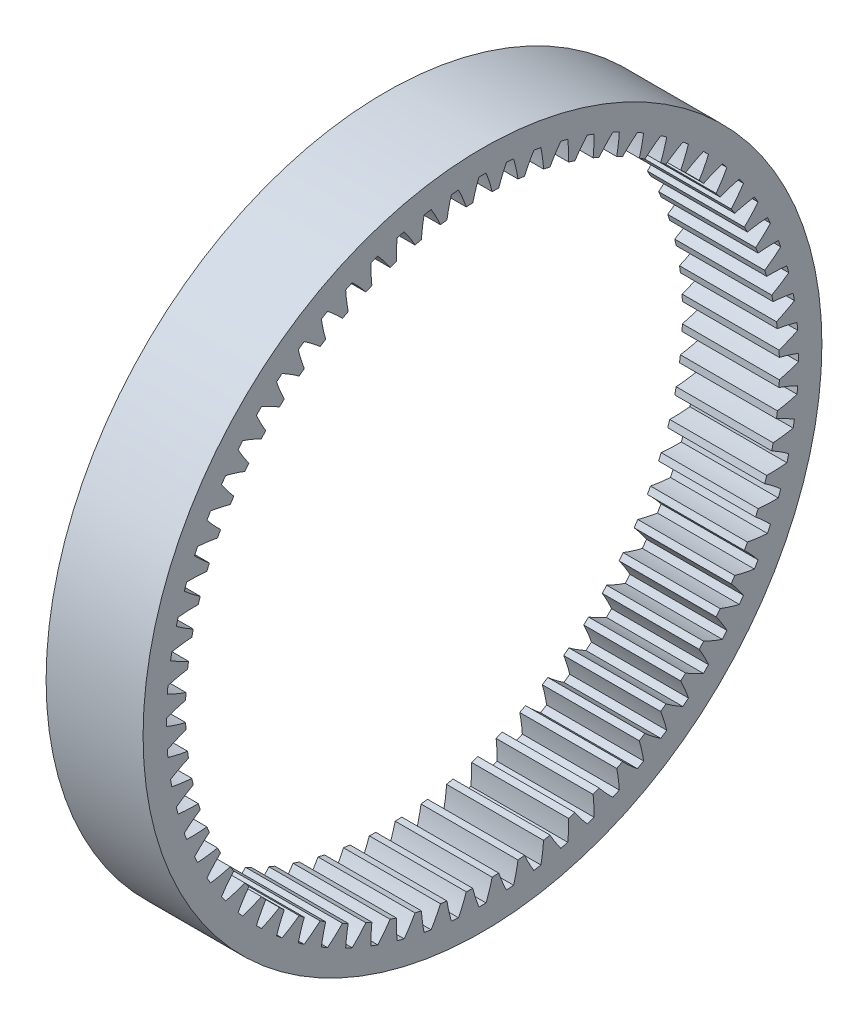
SolidWorks part; units mm, degrees
ref_plane "Plane1" through (0, 0, 0) normal (0, 0, 1) x (1, 0, 0)
ref_plane "Plane2" through (0, 0, 0) normal (0, 1, 0) x (1, 0, 0)
ref_plane "Plane3" through (0, 0, 0) normal (1, 0, 0) x (0, 0, -1)
sketch "HoldingSke" plane through (0, 0, 0) normal (0, 1, 0) x (1, 0, 0)
  line L0 (0, 0) -> (0.1766, -0.5435)
  line L1 (-15, 0) -> (100, 0) construction
  line L2 (0, 0) -> (-2.1039, 2.3779)
  line L3 (0, 0) -> (-11.863, 4.5341)
  line L4 (0, 0) -> (2.6687, 8.2133)
  line L5 (0, 0) -> (-23.7986, -8.8762)
  line L6 (0, 0) -> (-10.5278, -7.1032)
  line L7 (-2.1039, 2.3779) -> (3.3635, 27.1825)
  line L8 (-76.2, 4.1279) -> (-54.61, 4.1279)
  line L9 (-67.7845, 28.3722) -> (-49.3413, 33.142)
  line L10 (-76.2, 71.12) -> (104.1128, 71.12)
  line L11 (0, 0) -> (-20, 0)
  line L12 (-76.2, 101.6) -> (-76.147, 101.6)
  line L13 (24.9733, 27.94) -> (52.9518, 28.4284)
  line L14 (24.9733, 27.94) -> (24.9743, 27.94)
  line L15 (24.9733, 27.94) -> (100.4006, 29.5858)
  circle A0 centre (0, 0) radius 70
  circle A1 centre (0, 0) radius 12.7
  circle A2 centre (0, 0) radius 12.7
  dimension "MHD" = 25.4
  dimension "Hub_dia" = 25.4
  dimension "Diameter" = 140
  dimension "Num_teeth" = 72
  dimension "Pitch" = 0.5714
  dimension "Overall_len" = 25.4
  dimension "Show_teeth" = 72
  dimension "Thickness" = 12.7
  dimension "OAL" = 25.4001
  dimension "T_dim" = 21.59
  dimension "Ap" = 14.5
  dimension "H" = 19.05
  dimension "Pitch_radius" = 180.3128
  dimension "Width" = 20
  dimension "Backlash" = 0.053
  dimension "Addendum_fac" = 1
  dimension "Dedendum_fac" = 1.25
  dimension "Clearance_fac" = 0.25
  dimension "Dedendum_add" = 0.001
  dimension "Module" = 1.75
sketch "BasProSke" plane through (0, 0, 0) normal (0, 1, 0) x (1, 0, 0)
  line L0 (-10, 0) -> (60, 0) construction
  line L1 (0, 61.25) -> (0, 70)
  line L2 (0, 61.25) -> (20, 61.25)
  line L3 (20, 61.25) -> (20, 70)
  line L4 (20, 70) -> (0, 70)
  dimension "Diameter" = 140
  dimension "Thickness" = 20
  dimension "Inside_diameter" = 122.5
revolve "Base-Revolve" add sketch "BasProSke" angle 360 about L0
sketch "TooCutSke" plane through (0, 0, 0) normal (1, 0, 0) x (0, 0, -1)
  line L3 (1.5068, 62.982) -> (1.5068, 53.6633) construction
  line L4 (0, 0) -> (0, 59.563) construction
  line L5 (0, 0) -> (-2.9804, 68.2625) construction
  line L6 (-28.5939, 53.6978) -> (35.4123, 56.4924) construction
  circle A0 centre (0, 0) radius 63 construction
  circle A1 centre (0, 0) radius 65.1885 construction
  circle A2 centre (0, 0) radius 54.894 construction
  circle A3 centre (0, 0) radius 61.2246 construction
  arc A4 (2.0017, 61.1919) -> (0.7371, 65.1843) centre (-28.5939, 53.6978) ccw
  arc A5 (2.0017, 61.1919) -> (-2.0017, 61.1919) centre (0, 0) ccw
  arc A6 (0.7371, 65.1843) -> (-0.7371, 65.1843) centre (0, 0) ccw
  arc A7 (-0.7371, 65.1843) -> (-2.0017, 61.1919) centre (28.5939, 53.6978) ccw
  dimension "Pitch_dia" = 126
  dimension "Base_dia" = 109.7879
  dimension "Root_dia" = 130.377
  dimension "Overcut_dia" = 122.4492
  dimension "Flank_rad" = 31.5
  dimension "Half_ang" = 2.5
  dimension "Half_CT" = 1.5068
extrude "ToothCut" cut sketch "TooCutSke" along normal through all
fillet "Breaks" [suppressed] radius 0.175
fillet "RootFillets" [suppressed] radius 0.4385
pattern_circular "TeethCuts" count 72 every 5 about axis through (-10, 0, 0) along (1, 0, 0) of "RootFillets", "Breaks", "ToothCut"
equation "' \"Module@HoldingSke\" = 6.35"
equation "' \"Num_teeth@HoldingSke\" = 24"
equation "' \"Ap@HoldingSke\" =  14.5"
equation "' \"Ap@HoldingSke\" = 14.5"
equation "' \"Width@HoldingSke\" = 12"
equation "' \"Diameter@HoldingSke\" = 8 * 25.4"
equation "' \"Show_teeth@HoldingSke\" = 100"
equation "' \"Backlash@HoldingSke\" = 0.009 * 25.4"
equation "' \"Addendum_fac@HoldingSke\" = 1.0"
equation "' \"Dedendum_fac@HoldingSke\" = 1.25"
equation "' \"Dedendum_add@HoldingSke\" = 0.00005 * 25.4"
equation "' \"Clearance_fac@HoldingSke\" = 0.25"
equation "\"Pitch@HoldingSke\" = 1 / \"Module@HoldingSke\" "
equation "\"Overcut_dia@TooCutSke\" = (\"Num_teeth@HoldingSke\" - 2 * \"Addendum_fac@HoldingSke\") / \"Pitch@HoldingSke\" - 0.002 * 25.4"
equation "\"Pitch_dia@TooCutSke\" = \"Num_teeth@HoldingSke\" / \"Pitch@HoldingSke\""
equation "\"Base_dia@TooCutSke\" = \"Num_teeth@HoldingSke\" / \"Pitch@HoldingSke\" * cos((\"Ap@HoldingSke\"  * 3.14159265 / 180)) * 0.90"
equation "\"Root_dia@TooCutSke\" = \"Num_teeth@HoldingSke\"  / \"Pitch@HoldingSke\" + 2 *  \"Dedendum_fac@HoldingSke\"/ \"Pitch@HoldingSke\" + \"Dedendum_add@HoldingSke\" * 2"
equation "\"Half_ang@TooCutSke\" = 180 / \"Num_teeth@HoldingSke\""
equation "\"Half_CT@TooCutSke\" = \"Num_teeth@HoldingSke\" / \"Pitch@HoldingSke\" * sin((3.14159265 / 2 / \"Num_teeth@HoldingSke\")) / 2 + 10 * \"Backlash@HoldingSke\" / 4"
equation "\"Flank_rad@TooCutSke\" = \"Num_teeth@HoldingSke\" / \"Pitch@HoldingSke\" / 4"
equation "\"Radius@RootFillets\"= \"Clearance_fac@HoldingSke\" / \"Pitch@HoldingSke\" + \"Dedendum_add@HoldingSke\""
equation "\"Break_rad@Breaks\" = 0.02 / \"Pitch@HoldingSke\" * 5"
equation "\"Num_teeth@TeethCuts\" = int( \"Show_teeth@HoldingSke\" ) + 1"
equation "\"Num_teeth@TeethCuts\" = ((sgn( \"Num_teeth@TeethCuts\" - \"Num_teeth@HoldingSke\" )-1)*( \"Num_teeth@TeethCuts\" - \"Num_teeth@HoldingSke\" ))/-2+ \"Num_teeth@HoldingSke\""
equation "\"Num_teeth@TeethCuts\" = ((sgn( \"Num_teeth@TeethCuts\" - 2.0)+1)*( \"Num_teeth@TeethCuts\" - 2.0))/2 +2.0"
equation "\"Angle@TeethCuts\" = 360.0 / \"Num_teeth@HoldingSke\""
equation "\"Diameter@BasProSke\" = \"Num_teeth@HoldingSke\"  / \"Pitch@HoldingSke\" + 2 *  \"Dedendum_fac@HoldingSke\"/ \"Pitch@HoldingSke\" + \"Dedendum_add@HoldingSke\" * 2 + 0.002 * 25.4"
equation "\"Diameter@BasProSke\" = ((sgn( \"Diameter@BasProSke\"  - \"Diameter@HoldingSke\" )+1)*( \"Diameter@BasProSke\"  - \"Diameter@HoldingSke\" ))/2 + \"Diameter@HoldingSke\""
equation "\"Inside_diameter@BasProSke\" =  (\"Num_teeth@HoldingSke\" - 2 * \"Addendum_fac@HoldingSke\") / \"Pitch@HoldingSke\" "
equation "\"Thickness@BasProSke\"  = \"Width@HoldingSke\""
